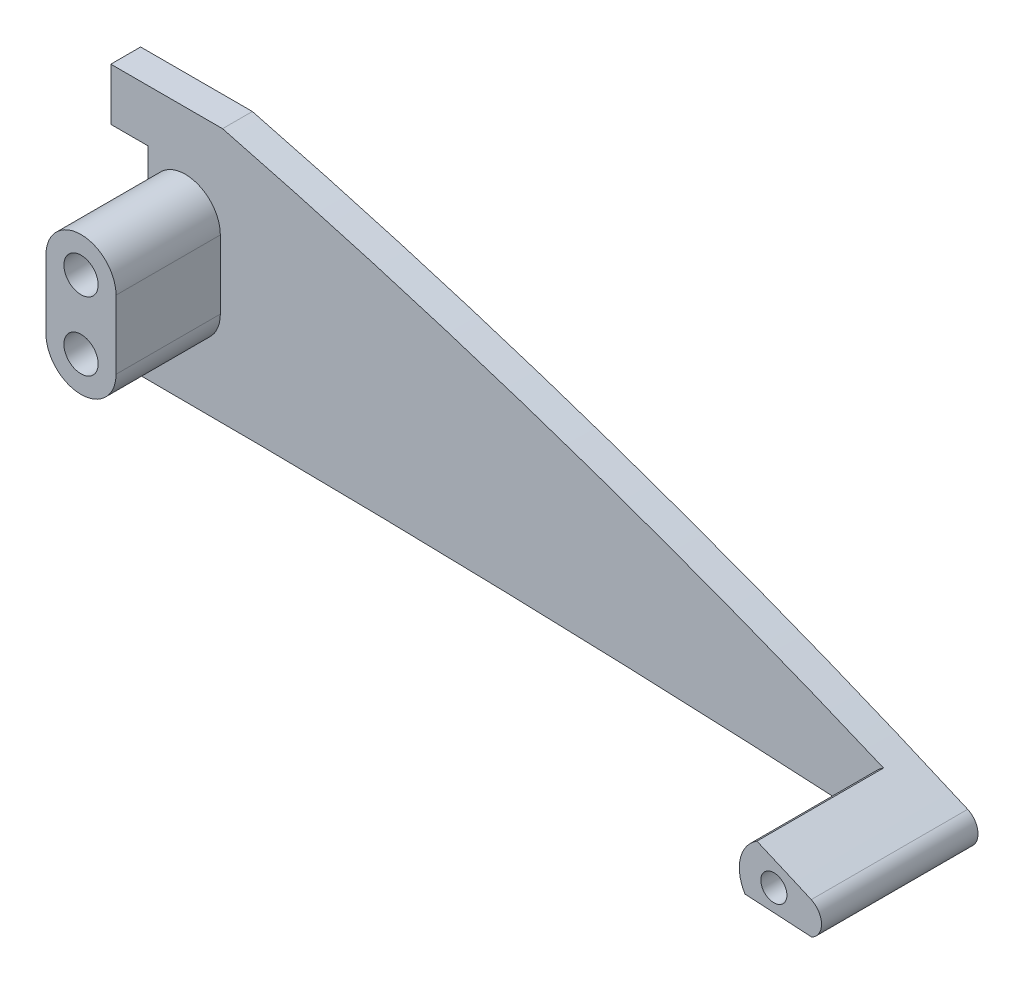
SolidWorks part; units mm, degrees
ref_plane "Płaszczyzna przednia" through (0, 0, 0) normal (0, 0, 1) x (1, 0, 0)
ref_plane "Płaszczyzna górna" through (0, 0, 0) normal (0, 1, 0) x (1, 0, 0)
ref_plane "Płaszczyzna prawa" through (0, 0, 0) normal (1, 0, 0) x (0, 0, -1)
sketch "Szkic2" plane through (0, 0, 0) normal (0, 0, 1) x (1, 0, 0)
  line L9 (15.2, 17.1) -> (15.2, 10.1)
  line L10 (-91.9323, 0) -> (51.5424, 0) construction
  line L11 (0, 24.6927) -> (0, -16.8499) construction
  line L12 (15.2, 17.1) -> (30.2, 17.1)
  line L16 (20.2, 10.1) -> (20.2, -10.1)
  line L19 (15.2, -17.1) -> (19.1974, -17.1)
  line L20 (15.2, 10.1) -> (20.2, 10.1)
  line L21 (15.2, -10.1) -> (20.2, -10.1)
  line L22 (15.2, -10.1) -> (15.2, -17.1)
  circle A5 centre (25.2, 4.6) radius 2.3
  circle A6 centre (25.2, -4.6) radius 2.3
  arc A8 (30.2, 17.1) -> (126.2167, -16.0095) centre (-123.1666, -583.436) cw
  arc A9 (19.1974, -17.1) -> (126.2693, -20.3334) centre (19.1974, -1791.5029) cw
  arc A10 (126.2167, -16.0095) -> (126.2693, -20.3334) centre (125.2, -18.1842) cw
  point P31 (20.2, 0)
  dimension "D8" = 5
  dimension "D12" = 4.6
  dimension "D1" = 34.2
  dimension "D2" = 105
  dimension "D3" = 5
  dimension "D4" = 20.2
  dimension "D5" = 15
  dimension "D6" = 3.9974
  dimension "D7" = 4.6
  dimension "D9" = 7
  dimension "D10" = 7
  dimension "D11" = 20.2
extrude "Dodanie-wyciągnięcie1" add sketch "Szkic2" along normal blind 4
sketch "Szkic3" plane through (0, 0, 4) normal (0, 0, 1) x (1, 0, 0)
  arc A0 (126.2693, -20.3334) -> (19.1974, -17.1) centre (19.1974, -1791.5029) ccw construction
  arc A1 (126.2167, -16.0095) -> (30.2, 17.1) centre (-123.1666, -583.436) ccw construction
  arc A2 (126.2693, -20.3334) -> (126.2167, -16.0095) centre (125.2, -18.1842) ccw construction
  arc A3 (126.2693, -20.3334) -> (117.3332, -19.8158) centre (19.1974, -1791.5029) ccw
  arc A4 (126.2167, -16.0095) -> (118.9224, -12.8594) centre (-123.1666, -583.436) ccw
  arc A5 (126.2693, -20.3334) -> (126.2167, -16.0095) centre (125.2, -18.1842) ccw
  circle A6 centre (121.2, -17.1334) radius 1.75
  arc A7 (117.3332, -19.8158) -> (118.9224, -12.8594) centre (121.606, -17.1322) cw
  dimension "D1" = 3.5
  dimension "D2" = 3.2
  dimension "D3" = 4
extrude "Dodanie-wyciągnięcie2" add sketch "Szkic3" along normal blind 17
sketch "Szkic5" plane through (0, 0, 4) normal (0, 0, 1) x (1, 0, 0)
  line L0 (25.2, -4.6) -> (25.2, 4.6) construction
  line L1 (20.5, -4.6) -> (20.5, 4.6)
  line L2 (29.9, -4.6) -> (29.9, 4.6)
  arc A0 (20.5, -4.6) -> (29.9, -4.6) centre (25.2, -4.6) ccw
  arc A1 (29.9, 4.6) -> (20.5, 4.6) centre (25.2, 4.6) ccw
  point P4 (25.2, 0)
  dimension "D2" = 4.7
  dimension "D1" = 9.2
extrude "Dodanie-wyciągnięcie3" add sketch "Szkic5" along normal blind 14
sketch "Szkic6" plane through (0, 0, 0) normal (0, 0, -1) x (-1, 0, 0)
  circle A0 centre (-25.2, -4.6) radius 2.3 construction
  circle A1 centre (-25.2, 4.6) radius 2.3 construction
  circle A2 centre (-25.2, -4.6) radius 2.3
  circle A3 centre (-25.2, 4.6) radius 2.3
  circle A4 centre (-121.2, -17.1334) radius 1.75 construction
  circle A5 centre (-121.2, -17.1334) radius 1.75
extrude "Wytnij-wyciągnięcie2" cut sketch "Szkic6" against normal through all
